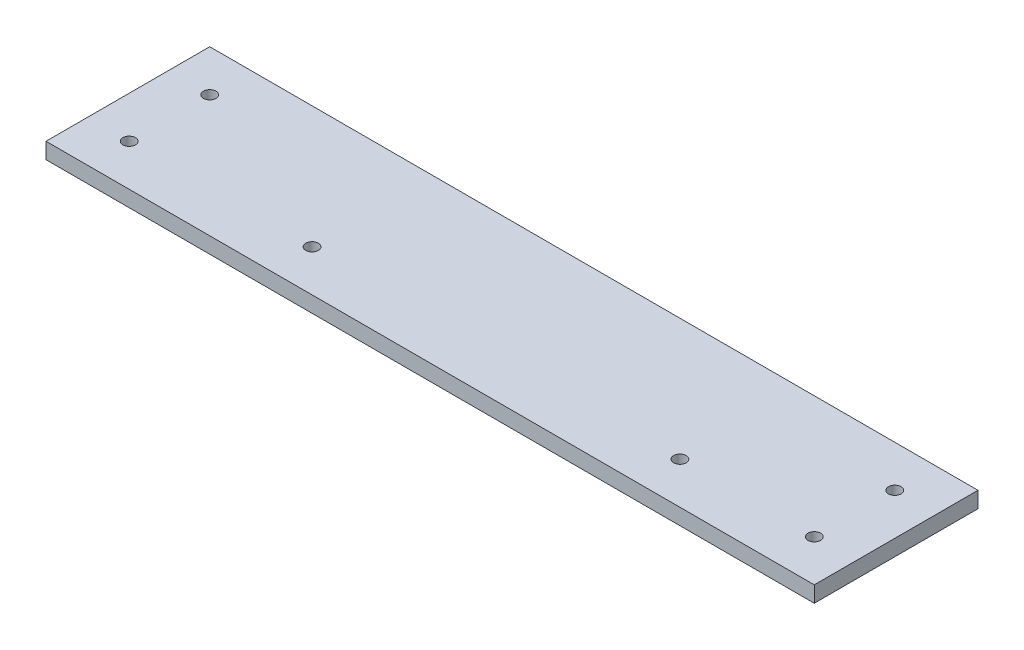
SolidWorks part; units mm, degrees
material "6061-T6 (SS)"
ref_plane "Front" through (0, 0, 0) normal (0, 0, 1) x (1, 0, 0)
ref_plane "Top" through (0, 0, 0) normal (0, 1, 0) x (1, 0, 0)
ref_plane "Right" through (0, 0, 0) normal (1, 0, 0) x (0, 0, -1)
sketch "Sketch1" plane through (0, 0, 0) normal (0, 1, 0) x (1, 0, 0)
  line L1 (-152.5, -32.5) -> (152.5, -32.5)
  line L2 (-152.5, -32.5) -> (-152.5, 32.5)
  line L3 (-152.5, 32.5) -> (152.5, 32.5)
  line L4 (152.5, -32.5) -> (152.5, 32.5)
  line L5 (-152.5, -32.5) -> (152.5, 32.5) construction
  line L6 (-152.5, 32.5) -> (152.5, -32.5) construction
  point P0 (0, 0)
  dimension "D1" = 65
  dimension "D2" = 305
extrude "Boss-Extrude1" add sketch "Sketch1" along normal mid plane 6.35
sketch "Sketch4" plane through (-2.5, 0, 0) normal (0, -1, 0) x (-1, 0, 0)
  line L0 (133.48, -3.48) -> (120.98, -3.48) construction
  line L1 (120.98, -3.48) -> (-2.5, -3.48) construction
  line L2 (143.285, -15.98) -> (145.98, -15.98) construction
  line L3 (-2.5, 0) -> (49997.5, 0) construction
  line L4 (120.98, -15.98) -> (123.675, -15.98) construction
  line L5 (133.48, -3.48) -> (133.48, -6.175) construction
  line L6 (120.98, 3.48) -> (120.98, 15.98) construction
  line L7 (120.98, -3.48) -> (120.98, -15.98) construction
  line L8 (133.48, 3.48) -> (133.48, 6.175) construction
  line L9 (120.98, 15.98) -> (123.675, 15.98) construction
  line L10 (143.285, 15.98) -> (145.98, 15.98) construction
  line L11 (120.98, 3.48) -> (-2.5, 3.48) construction
  line L12 (133.48, 3.48) -> (120.98, 3.48) construction
  line L14 (133.48, -25.785) -> (133.48, -28.48) construction
  line L15 (-2.5, 3.48) -> (-2.5, -3.48) construction
  line L16 (150, -32.5) -> (-155, -32.5) construction
  line L17 (150, 32.5) -> (150, -32.5) construction
  circle A1 centre (133.48, -15.98) radius 2.5
  circle A2 centre (133.48, -15.98) radius 12.5 construction
  circle A4 centre (133.48, -15.98) radius 9.805 construction
  circle A5 centre (133.48, 15.98) radius 9.805 construction
  circle A6 centre (133.48, 15.98) radius 12.5 construction
  circle A7 centre (133.48, 15.98) radius 2.5
  dimension "D1" = 15.98
  dimension "D2" = 5
  dimension "D3" = 25
  dimension "D4" = 19.61
  dimension "D5" = 16.52
  dimension "D6" = 16.52
  dimension "D7" = 135.98
extrude "Cut-Extrude2" cut sketch "Sketch4" against normal through all both and the other way through all
mirror "Mirror2" about plane through (0, 0, 0) normal (1, 0, 0) of "Cut-Extrude2"
sketch "Sketch5" plane through (0, 3.175, 0) normal (0, 1, 0) x (1, 0, 0)
  line L0 (135.98, -15.98) -> (37.6939, -15.98) construction
  line L1 (152.5, -32.5) -> (152.5, 32.5) construction
  circle A0 centre (82.64, -15.98) radius 2.5
  circle A1 centre (-63.41, -15.98) radius 2.5
  circle A2 centre (-135.98, -15.98) radius 2.5 construction
  circle A3 centre (135.98, -15.98) radius 2.5 construction
  circle A5 centre (135.98, -15.98) radius 2.5 construction
  dimension "D1" = 5
  dimension "D5" = 72.57
  dimension "D2" = 53.34
  dimension "D3" = 146.05
  dimension "D4" = 69.86
extrude "Cut-Extrude3" cut sketch "Sketch5" against normal through all both and the other way through all
